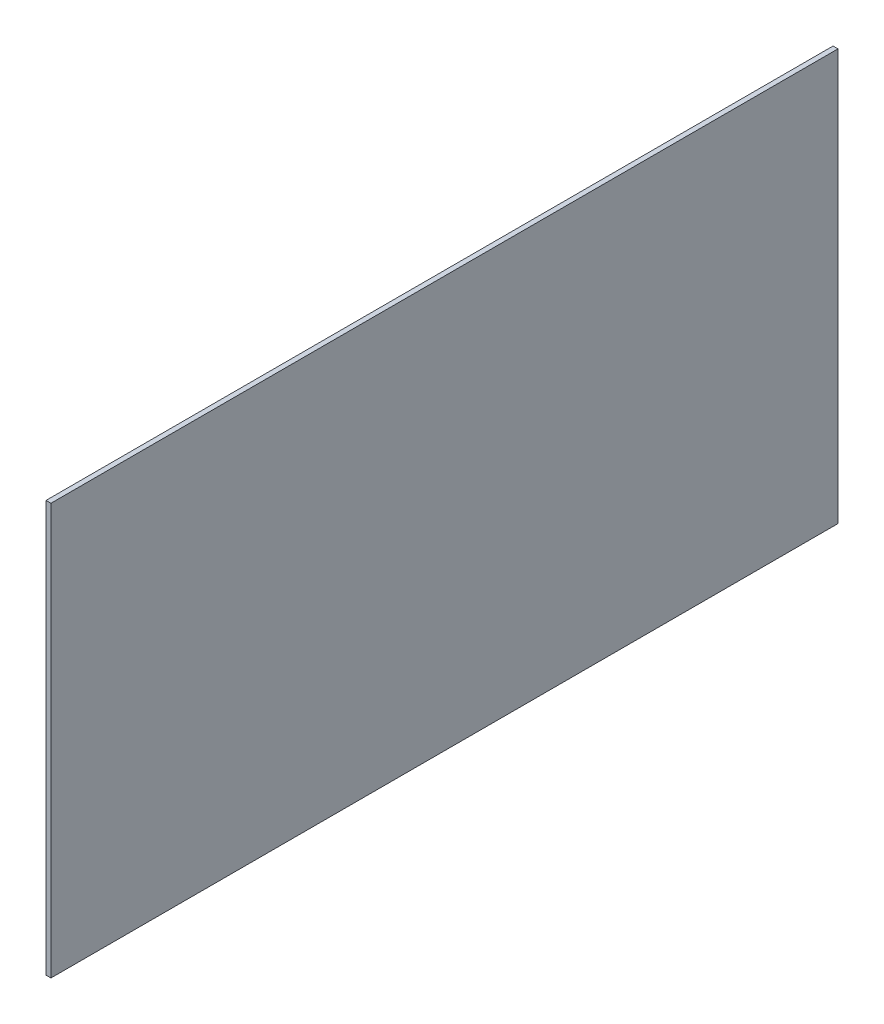
SolidWorks part; units mm, degrees
material "ASTM A36 Steel"
ref_plane "Front Plane" through (0, 0, 0) normal (0, 0, 1) x (1, 0, 0)
ref_plane "Top Plane" through (0, 0, 0) normal (0, 1, 0) x (1, 0, 0)
ref_plane "Right Plane" through (0, 0, 0) normal (1, 0, 0) x (0, 0, -1)
sketch "Sketch1" plane through (0, 0, 0) normal (1, 0, 0) x (0, 0, -1)
  line L0 (0, 0) -> (0, 349.25) construction
  line L1 (0, 0) -> (-596.9, 0) construction
  line L2 (-115.57, 0) -> (-115.57, 222.25)
  line L3 (-115.57, 222.25) -> (-541.02, 222.25)
  line L4 (-541.02, 222.25) -> (-541.02, 0)
  line L5 (-596.9, 0) -> (-115.57, 0)
  dimension "D1" = 349.25
  dimension "D2" = 596.9
  dimension "D3" = 222.25
  dimension "D4" = 115.57
  dimension "D5" = 425.45
extrude "Boss-Extrude1" add sketch "Sketch1" along normal blind 2.667 contours L4 L5 L2 L3
